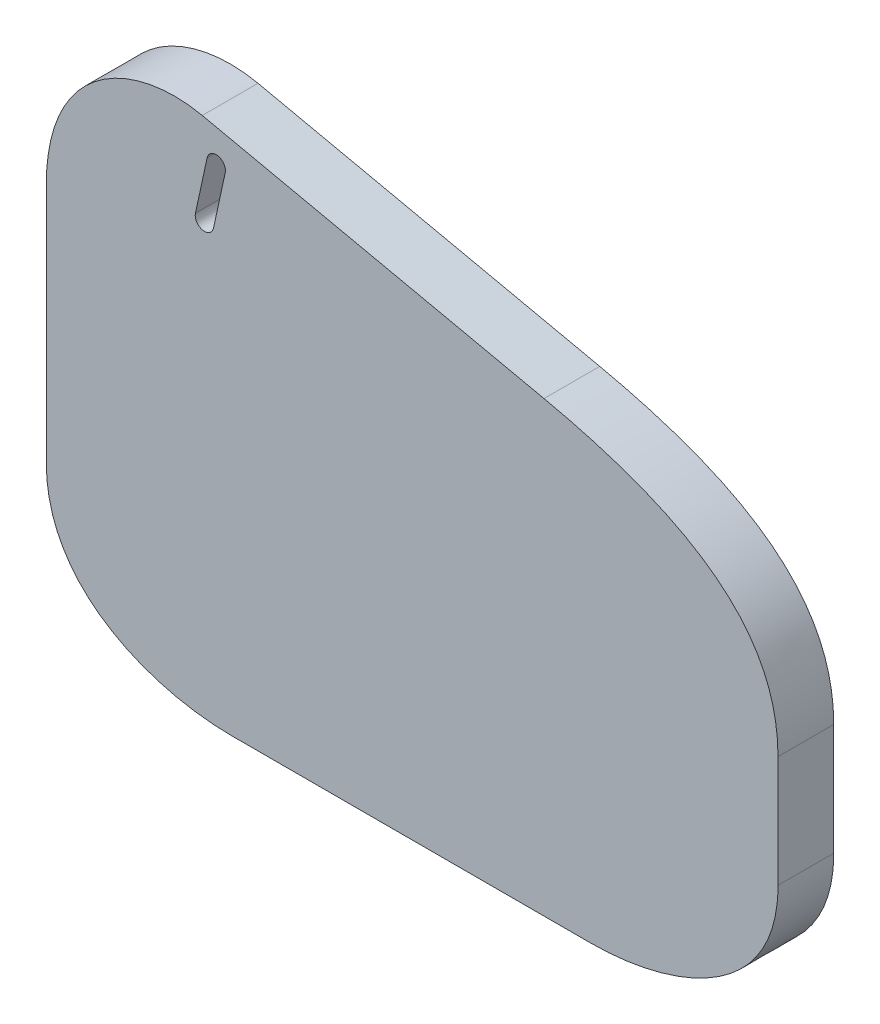
SolidWorks part; units mm, degrees
ref_plane "Спереди" through (0, 0, 0) normal (0, 0, 1) x (1, 0, 0)
ref_plane "Сверху" through (0, 0, 0) normal (0, 1, 0) x (1, 0, 0)
ref_plane "Справа" through (0, 0, 0) normal (1, 0, 0) x (0, 0, -1)
sketch "Эскиз1_fr" plane through (0, 0, 0) normal (0, 0, 1) x (1, 0, 0)
  line L0 (0, 0) -> (0, 20)
  line L1 (-41.9869, 54.6497) -> (-103.3012, 67.9789)
  line L2 (-131.2925, 43.0977) -> (-131.2925, 0)
  line L3 (-33.5451, -25.7698) -> (-97.9695, -25.7698)
  spline S0 degree 3 poles (0, 20) (0, 38.146) (-14.2095, 48.6111) (-41.9869, 54.6497) knots 0 0 0 0 1 1 1 1
  spline S1 degree 3 poles (-103.3012, 67.9789) (-115.5, 70.6308) (-131.2925, 63.3933) (-131.2925, 43.0977) knots 0 0 0 0 1 1 1 1
  spline S2 degree 3 poles (-33.5451, -25.7698) (-19.4449, -25.7698) (0, -19.0638) (0, 0) knots 0 0 0 0 1 1 1 1
  spline S3 degree 3 poles (-97.9695, -25.7698) (-112.0112, -25.7698) (-131.2925, -19.0252) (-131.2925, 0) knots 0 0 0 0 1 1 1 1
  dimension "D1" = 20
extrude "Бобышка-Вытянуть1" add sketch "Эскиз1_fr" along normal blind 10
sketch "Эскиз2_fr" plane through (0, 0, 0) normal (0, 0, -1) x (-1, 0, 0)
  line L2 (100.8084, 61.4805) -> (102.9069, 51.8273) construction
  line L3 (102.4293, 61.8329) -> (104.5278, 52.1796)
  line L4 (99.1876, 61.1282) -> (101.2861, 51.4749)
  arc A0 (102.4293, 61.8329) -> (99.1876, 61.1282) centre (100.8084, 61.4805) ccw
  arc A1 (101.2861, 51.4749) -> (104.5278, 52.1796) centre (102.9069, 51.8273) ccw
  point P4 (101.8577, 56.6539)
extrude "Вырез-Вытянуть1" cut sketch "Эскиз2_fr" against normal through all contours L3 A1 L4 A0
curve "Объединенная кривая1"
